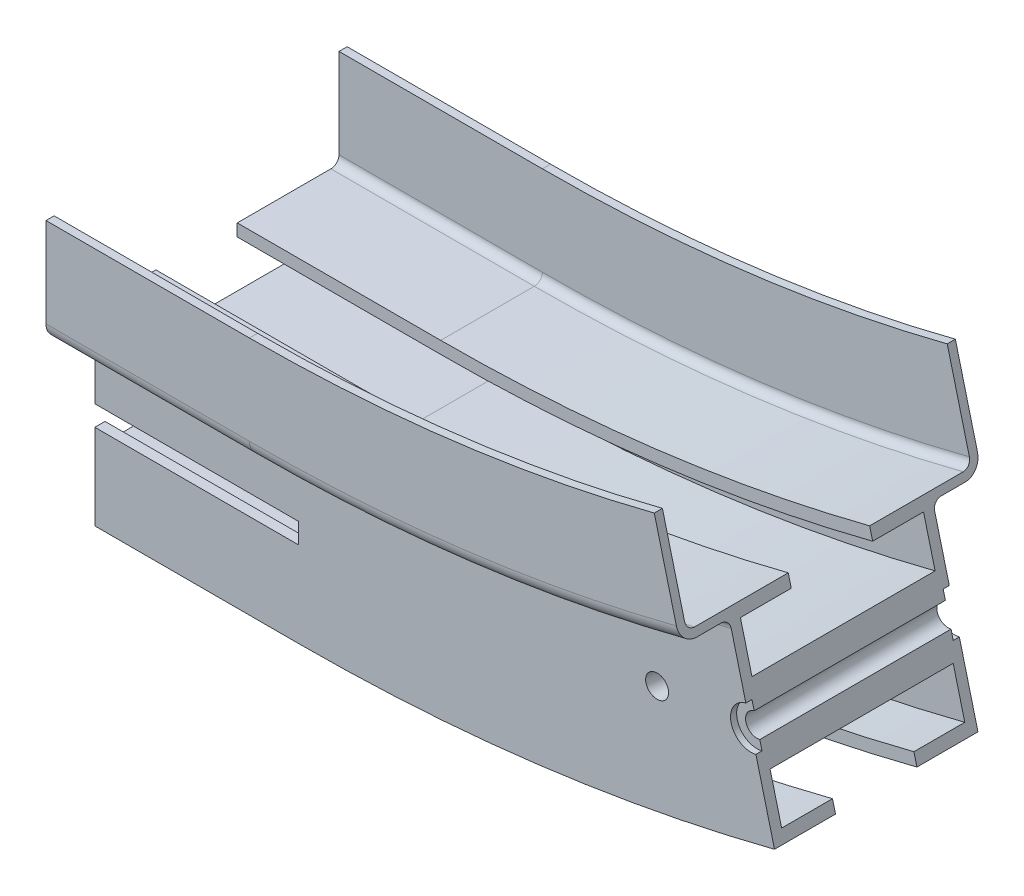
SolidWorks part; units mm, degrees
material "ABS generico"
ref_plane "Piano frontale" through (0, 0, 0) normal (0, 0, 1) x (1, 0, 0)
ref_plane "Piano superiore" through (0, 0, 0) normal (0, 1, 0) x (1, 0, 0)
ref_plane "Piano destro" through (0, 0, 0) normal (1, 0, 0) x (0, 0, -1)
sketch "Schizzo1" plane through (0, 0, 0) normal (1, 0, 0) x (0, 0, -1)
  line L0 (-10, -23.5) -> (-10, -20.5)
  line L1 (-10, -20.5) -> (-22.5, -20.5)
  line L2 (-22.5, -20.5) -> (-22.5, -9)
  line L3 (-22.5, -9) -> (22.5, -9)
  line L4 (22.5, -9) -> (22.5, -20.5)
  line L5 (22.5, -20.5) -> (10, -20.5)
  line L6 (10, -20.5) -> (10, -23.5)
  line L7 (10, -23.5) -> (25, -23.5)
  line L8 (25, -23.5) -> (25, -2.5)
  line L9 (27, 21.5) -> (33, 21.5)
  line L10 (37, 25.5) -> (37, 47.5)
  line L11 (37, 47.5) -> (35, 47.5)
  line L12 (35, 47.5) -> (35, 25.5)
  line L13 (33, 23.5) -> (10, 23.5)
  line L14 (10, 23.5) -> (10, 20.5)
  line L15 (10, 20.5) -> (22.5, 20.5)
  line L16 (22.5, 20.5) -> (22.5, 9)
  line L17 (22.5, 9) -> (-22.5, 9)
  line L18 (-22.5, 9) -> (-22.5, 20.5)
  line L19 (-22.5, 20.5) -> (-10, 20.5)
  line L20 (-10, 20.5) -> (-10, 23.5)
  line L21 (-10, 23.5) -> (-33, 23.5)
  line L22 (-35, 25.5) -> (-35, 47.5)
  line L23 (-35, 47.5) -> (-37, 47.5)
  line L24 (-37, 47.5) -> (-37, 25.5)
  line L25 (-33, 21.5) -> (-27, 21.5)
  line L26 (-25, 19.5) -> (-25, 2.5)
  line L27 (-25, -23.5) -> (-10, -23.5)
  line L28 (-12.5, 0) -> (-25, 0) construction
  line L29 (-22.5, 7) -> (-12.5, 7)
  line L30 (-22.5, 7) -> (-22.5, 2.5)
  line L31 (-22.5, -7) -> (-12.5, -7)
  line L32 (-12.5, 7) -> (-12.5, -7)
  line L33 (-12.5, 0) -> (12.5, 0) construction
  line L34 (12.5, 7) -> (22.5, 7)
  line L35 (12.5, 7) -> (12.5, -7)
  line L36 (12.5, -7) -> (22.5, -7)
  line L37 (22.5, 7) -> (22.5, 2.5)
  line L38 (-25, 2.5) -> (-22.5, 2.5)
  line L39 (-8.5, 7) -> (8.5, 7)
  line L40 (-10, 5.5) -> (-10, -5.5)
  line L41 (-8.5, -7) -> (8.5, -7)
  line L42 (10, 5.5) -> (10, -5.5)
  line L43 (-25, -2.5) -> (-22.5, -2.5)
  line L44 (-22.5, -2.5) -> (-22.5, -7)
  line L45 (22.5, 2.5) -> (25, 2.5)
  line L46 (22.5, -2.5) -> (25, -2.5)
  line L47 (22.5, -2.5) -> (22.5, -7)
  line L48 (-25, -2.5) -> (-25, -23.5)
  line L49 (25, 2.5) -> (25, 19.5)
  line L50 (12.5, 0) -> (25, 0) construction
  line L51 (-25, -2.5) -> (-25, 2.5) construction
  line L52 (25, -2.5) -> (25, 2.5) construction
  arc A0 (-27, 21.5) -> (-25, 19.5) centre (-27, 19.5) cw
  arc A1 (-37, 25.5) -> (-33, 21.5) centre (-33, 25.5) ccw
  arc A2 (-35, 25.5) -> (-33, 23.5) centre (-33, 25.5) ccw
  arc A3 (33, 23.5) -> (35, 25.5) centre (33, 25.5) ccw
  arc A4 (37, 25.5) -> (33, 21.5) centre (33, 25.5) cw
  arc A5 (25, 19.5) -> (27, 21.5) centre (27, 19.5) cw
  arc A6 (-8.5, -7) -> (-10, -5.5) centre (-8.5, -5.5) cw
  arc A7 (8.5, -7) -> (10, -5.5) centre (8.5, -5.5) ccw
  arc A8 (10, 5.5) -> (8.5, 7) centre (8.5, 5.5) ccw
  arc A9 (-8.5, 7) -> (-10, 5.5) centre (-8.5, 5.5) ccw
  point P57 (-10, 0)
  point P74 (0, 0)
  point P76 (-22.5, -4.75)
  dimension "D10" = 4
  dimension "D11" = 2
  dimension "D19" = 1.5
  dimension "D1" = 50
  dimension "D2" = 18
  dimension "D3" = 21
  dimension "D4" = 15
  dimension "D5" = 3
  dimension "D6" = 4.5
  dimension "D7" = 11.5
  dimension "D8" = 19
  dimension "D9" = 45
  dimension "D12" = 74
  dimension "D13" = 2
  dimension "D14" = 24
  dimension "D15" = 27
  dimension "D16" = 2.5
  dimension "D17" = 2.5
  dimension "D18" = 2.5
  dimension "D20" = 2.5
  dimension "D21" = 2.5
  dimension "D22" = 2.5
  dimension "D23" = 10
extrude "Estrusione-Estrusione1" add sketch "Schizzo1" along normal blind 50
chamfer "Smusso1" distance 1.6 angle 45 8 edges at (25, 7, -12.5) (25, 7, -22.5) (25, -7, -22.5) (25, -7, -12.5) (25, -7, 22.5) (25, 7, 22.5) (25, 7, 12.5) (25, -7, 12.5)
sketch "Schizzo2" plane through (50, 0, 0) normal (1, 0, 0) x (0, 0, -1)
  line L0 (-10, -23.5) -> (-25, -23.5)
  line L1 (-25, -23.5) -> (-25, 19.5)
  line L2 (-10, -23.5) -> (-10, -20.5)
  line L3 (-10, -20.5) -> (-22.5, -20.5)
  line L4 (-22.5, -20.5) -> (-22.5, -9)
  line L5 (-22.5, -9) -> (22.5, -9)
  line L6 (22.5, -9) -> (22.5, -20.5)
  line L7 (22.5, -20.5) -> (10, -20.5)
  line L8 (10, -20.5) -> (10, -23.5)
  line L9 (10, -23.5) -> (25, -23.5)
  line L10 (25, -23.5) -> (25, 19.5)
  line L11 (27, 21.5) -> (33, 21.5)
  line L12 (37, 25.5) -> (37, 47.5)
  line L13 (37, 47.5) -> (35, 47.5)
  line L14 (35, 47.5) -> (35, 25.5)
  line L15 (33, 23.5) -> (10, 23.5)
  line L16 (10, 23.5) -> (10, 20.5)
  line L17 (10, 23.5) -> (10, 20.5) construction
  line L18 (10, 20.5) -> (22.5, 20.5) construction
  line L19 (10, 20.5) -> (22.5, 20.5)
  line L20 (22.5, 20.5) -> (22.5, 9)
  line L21 (22.5, 9) -> (-22.5, 9)
  line L22 (-22.5, 9) -> (-22.5, 20.5)
  line L23 (-22.5, 20.5) -> (-10, 20.5)
  line L24 (-10, 20.5) -> (-10, 23.5)
  line L25 (-10, 23.5) -> (-33, 23.5)
  line L26 (-35, 25.5) -> (-35, 47.5)
  line L27 (-35, 47.5) -> (-37, 47.5)
  line L28 (-37, 47.5) -> (-37, 25.5)
  line L29 (-37, 47.5) -> (-37, 25.5) construction
  line L30 (-33, 21.5) -> (-27, 21.5)
  line L31 (-89.8861, 450) -> (122.001, 450) construction
  line L32 (-25, 0) -> (25, 0) construction
  arc A0 (25, 19.5) -> (27, 21.5) centre (27, 19.5) cw
  arc A1 (33, 21.5) -> (37, 25.5) centre (33, 25.5) ccw
  arc A2 (33, 21.5) -> (37, 25.5) centre (33, 25.5) ccw construction
  arc A3 (35, 25.5) -> (33, 23.5) centre (33, 25.5) cw
  arc A4 (-33, 23.5) -> (-35, 25.5) centre (-33, 25.5) cw
  arc A5 (-37, 25.5) -> (-33, 21.5) centre (-33, 25.5) ccw construction
  arc A6 (-37, 25.5) -> (-33, 21.5) centre (-33, 25.5) ccw
  arc A7 (-27, 21.5) -> (-25, 19.5) centre (-27, 19.5) cw
  dimension "D1" = 450
revolve "Rivoluzione1" add sketch "Schizzo2" angle 14.31 about L31
sketch "Schizzo7" plane through (154.72, 39.4664, 0) normal (0.969, 0.2472, 0) x (0, 0, -1)
  line L0 (-25, -26.3207) -> (25, -26.3207) construction
  line L1 (-25, -6.8207) -> (-25, -49.8207) construction
  line L2 (25, -49.8207) -> (25, -6.8207) construction
  line L3 (-22.5, -35.3207) -> (22.5, -35.3207) construction
  dimension "D1" = 9
sketch "Schizzo18" plane through (154.72, 39.4664, 0) normal (0.969, 0.2472, 0) x (0, 0, -1)
  line L0 (-25, -26.3207) -> (25, -26.3207)
  line L1 (25, -26.3207) -> (25, -21.3207)
  line L2 (25, -49.8207) -> (25, -6.8207) construction
  line L3 (25, -21.3207) -> (23.5, -21.3207)
  line L4 (23.5, -21.3207) -> (23.5, -23.5207)
  line L5 (23.5, -23.5207) -> (-23.5, -23.5207)
  line L6 (-23.5, -23.5207) -> (-23.5, -21.3207)
  line L7 (-23.5, -21.3207) -> (-25, -21.3207)
  line L8 (-25, -6.8207) -> (-25, -49.8207) construction
  line L9 (-25, -21.3207) -> (-25, -26.3207)
  dimension "D1" = 2.8
  dimension "D2" = 5
  dimension "D3" = 1.5
revolve "Taglia-Rivoluzione1" cut sketch "Schizzo18" angle 360 about L0
sketch "Schizzo20" plane through (0, 0, 0) normal (0, 1, 0) x (1, 0, 0)
  line L0 (161.2257, 25) -> (161.2257, 150) construction
  circle A0 centre (161.2257, 150) radius 75
  point P3 (161.2257, 150)
  dimension "D4" = 150
  dimension "D1" = 125
curve "Elica/Spirale2" pitch 120 height 30 turns 0.25
sketch3d "Schizzo3D3"
  line L0 (161.2257, 0, -150) -> (161.2257, 103.5709, -150) construction
  line L1 (161.2257, 0, -150) -> (161.2257, 0, 97.6439) construction
  line L2 (161.2257, 0, -150) -> (144.4754, 0, -22.769) construction
  line L3 (151.4362, 11.5, -75.6418) -> (161.2257, 11.5, -150) construction
  line L4 (151.4362, 11.5, -75.6418) -> (138.1865, 11.5, 25) construction
  line L5 (138.1865, 11.5, 25) -> (130.2353, 11.5, 85.3949) construction
  line L6 (105.8885, 11.5, 82.1896) -> (154.5821, 11.5, 88.6003) construction
  spline S0 degree 3 poles (111.0409, 0, -94.2641) (114.2796, 1.1098, -91.348) (121.2812, 3.3339, -86.0711) (132.9867, 6.6665, -80.1077) (145.553, 10, -76.2654) (158.5948, 13.3333, -74.6642) (171.7168, 16.6667, -75.3519) (184.5198, 20, -78.3076) (196.6157, 23.3335, -83.4424) (207.6337, 26.6661, -90.5966) (214.0454, 28.8902, -96.5765) (216.9615, 30, -99.8152) knots 0 0 0 0 0.111111 0.222222 0.333333 0.444444 0.555556 0.666667 0.777778 0.888889 1 1 1 1 construction
  point P13 (130.2353, 11.5, 85.3949)
  dimension "D1" = 7.5
ref_plane "Piano6" through (-8.8321, 0, 67.0864) normal (-0.1305, 0, 0.9914) x (0.9914, 0, 0.1305)
hole_wizard "Foro per Vite M5-2" positions "Schizzo21" profile "Schizzo22" hole size "M5" standard "ISO"
sketch "Schizzo21" plane through (-8.8321, 0, 67.0864) normal (-0.1305, 0, 0.9914) x (0.9914, 0, 0.1305)
  point P0 (140.2674, 11.5)
sketch "Schizzo22" plane through (130.2353, 11.5, 85.3949) normal (0, 1, 0) x (0.9914, 0, 0.1305)
  line L0 (0, 0) -> (0, 121.6824)
  line L1 (0, 121.6824) -> (2.8, 120)
  line L2 (2.8, 120) -> (2.8, 0)
  line L5 (2.8, 0) -> (0, 0)
  line L10 (0, 121.6824) -> (-2.8, 120) construction
  line L11 (0, -6.35) -> (0, 107.95) construction
  dimension "Hole Dia." = 5.6
  dimension "Hole Depth" = 120
  dimension "Drill Angle" = 118
